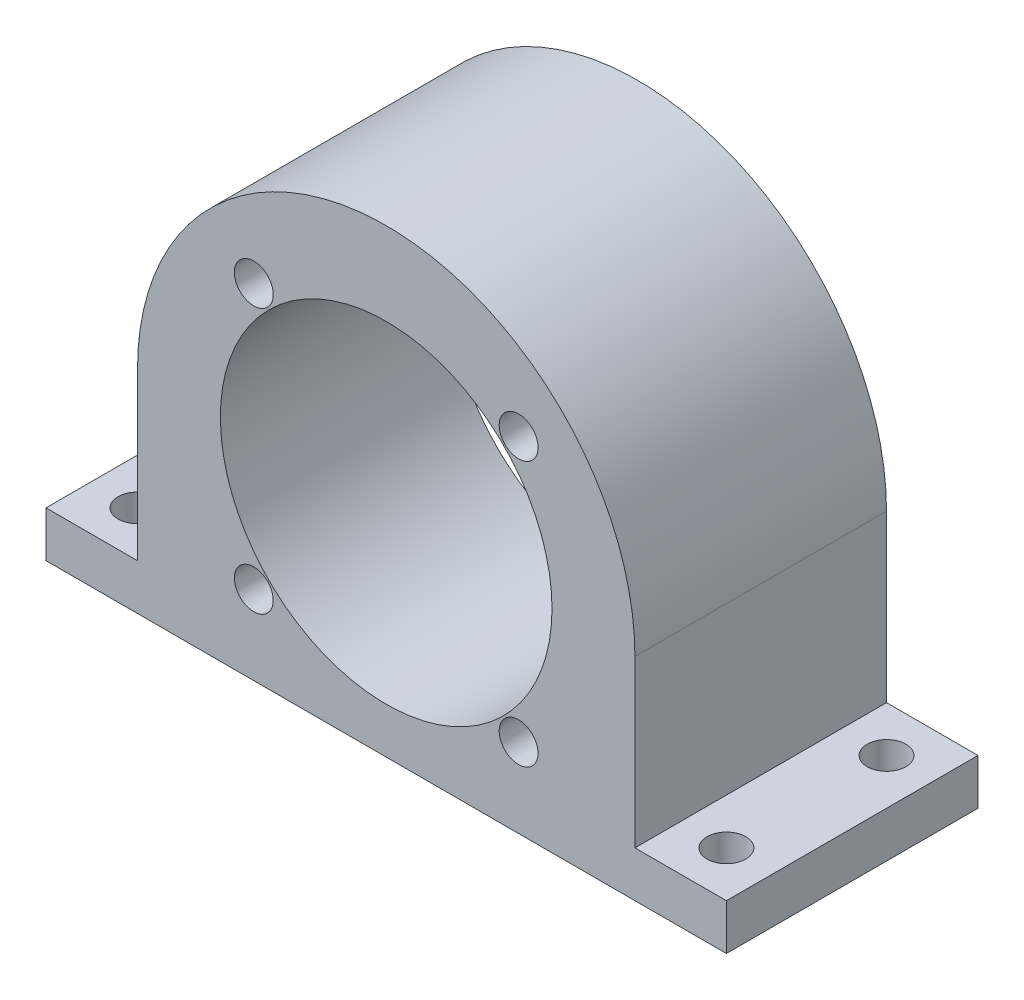
SolidWorks part; units mm, degrees
ref_plane "Front Plane" through (0, 0, 0) normal (0, 0, 1) x (1, 0, 0)
ref_plane "Top Plane" through (0, 0, 0) normal (0, 1, 0) x (1, 0, 0)
ref_plane "Right Plane" through (0, 0, 0) normal (1, 0, 0) x (0, 0, -1)
sketch "Sketch2" plane through (0, 0, 0) normal (0, 0, 1) x (1, 0, 0)
  line L0 (-21.75, 0) -> (21.75, 0)
  line L1 (-21.75, 18.5) -> (-21.75, 0)
  line L2 (21.75, 18.5) -> (21.75, 0)
  circle A0 centre (0, 18.5) radius 14.5
  arc A1 (21.75, 18.5) -> (-21.75, 18.5) centre (0, 18.5) ccw
  circle A2 centre (0, 18.5) radius 21.75 construction
  dimension "D1" = 29
  dimension "D3" = 18.5
  dimension "D4" = 43.5
extrude "Boss-Extrude1" add sketch "Sketch2" along normal mid plane 22
sketch "Sketch4" plane through (-21.75, 0, 0) normal (-1, 0, 0) x (0, 0, 1)
  line L1 (-11, 0) -> (-3, 0)
  line L2 (-11, 0) -> (-11, 4)
  line L3 (-11, 4) -> (-3, 4)
  line L4 (-3, 0) -> (-3, 4)
  dimension "D1" = 4
  dimension "D2" = 8
extrude "Boss-Extrude2" add sketch "Sketch4" along normal blind 8
hole_wizard "M3 Clearance Hole1" positions "Sketch6" profile "Sketch7" hole size "M3" standard "ANSI Metric" end condition through all
sketch "Sketch6" plane through (0, 4, 0) normal (0, 1, 0) x (1, 0, 0)
  line L0 (-21.75, 11) -> (-29.75, 3) construction
  line L2 (-29.75, 11) -> (-21.75, 3) construction
  point P13 (-25.75, 7)
sketch "Sketch7" plane through (-25.75, 4, -7) normal (1, 0, 0) x (0, 0, 1)
  line L0 (0, 0) -> (0, 4)
  line L1 (0, 4) -> (1.7, 4)
  line L2 (1.7, 4) -> (1.7, 0)
  line L5 (1.7, 0) -> (0, 0)
  line L11 (0, -6.35) -> (0, 107.95) construction
  dimension "Thru Hole Dia." = 3.4
  dimension "Thru Hole Depth" = 4
mirror "Mirror1" about plane through (0, 0, 0) normal (0, 0, 1) of "M3 Clearance Hole1", "Boss-Extrude2"
mirror "Mirror2" about plane through (0, 0, 0) normal (1, 0, 0) of "Mirror1", "Boss-Extrude2", "M3 Clearance Hole1"
sketch "Sketch8" plane through (0, 0, -11) normal (0, 0, -1) x (-1, 0, 0)
  line L4 (-8.6202, 27.1202) -> (5.7203, 12.7797) construction
  line L5 (0, 0) -> (0, 44.258) construction
  line L10 (29.75, 0) -> (-29.75, 0) construction
  line L11 (-14.3189, 27.3388) -> (-12.6202, 25.6401)
  line L12 (-8.8388, 32.8189) -> (-7.1401, 31.1202)
  line L13 (0, 18.5) -> (7.5499, 26.0499) construction
  circle A5 centre (0, 18.5) radius 14.5 construction
  arc A7 (-14.3189, 27.3388) -> (-8.8388, 32.8189) centre (-11.5789, 30.0789) cw
  arc A9 (-7.1401, 31.1202) -> (-12.6202, 25.6401) centre (0, 18.5) ccw
  point P0 (0, 18.5)
  point P14 (-8.8388, 27.3388)
  point P24 (-14.3189, 32.8189)
  dimension "D1" = 45
  dimension "D2" = 7.75
  dimension "D3" = 40.5
extrude "Cut-Extrude1" cut sketch "Sketch8" against normal blind 2
hole_wizard "M3 Clearance Hole2" positions "Sketch9" profile "Sketch10" hole size "M3" standard "ANSI Metric"
sketch "Sketch9" plane through (0, 0, -9) normal (0, 0, -1) x (-1, 0, 0)
  point P0 (-11.5789, 30.0789)
sketch "Sketch10" plane through (11.5789, 30.0789, -9) normal (1, 0, 0) x (0, 1, 0)
  line L0 (0, 0) -> (0, 21.0205)
  line L1 (0, 21.0205) -> (1.7, 19.999)
  line L2 (1.7, 19.999) -> (1.7, 0)
  line L5 (1.7, 0) -> (0, 0)
  line L10 (0, 21.0205) -> (-1.7, 19.999) construction
  line L11 (0, -6.35) -> (0, 107.95) construction
  dimension "Hole Dia." = 3.4
  dimension "Hole Depth" = 19.999
  dimension "Drill Angle" = 118
pattern_circular "CirPattern1" count 4 over 360 about axis through (0, 18.5, 0) along (0, 0, 1) of "Cut-Extrude1", "M3 Clearance Hole2"
sketch "Sketch11" plane through (0, 0, 0) normal (1, 0, 0) x (0, 0, -1)
  line L0 (-3, 4) -> (3, 4)
  line L1 (3, 0) -> (3, 4) construction
  line L2 (3, 0) -> (3, 4) construction
  line L3 (3, 4) -> (3, 0)
  line L4 (3, 0) -> (-3, 0)
  line L5 (-3, 0) -> (-3, 4)
extrude "Boss-Extrude3" add sketch "Sketch11" along normal up to surface and the other way up to surface up to face at (29.75, 2, 7) other way up to face at (-29.75, 2, 7)
